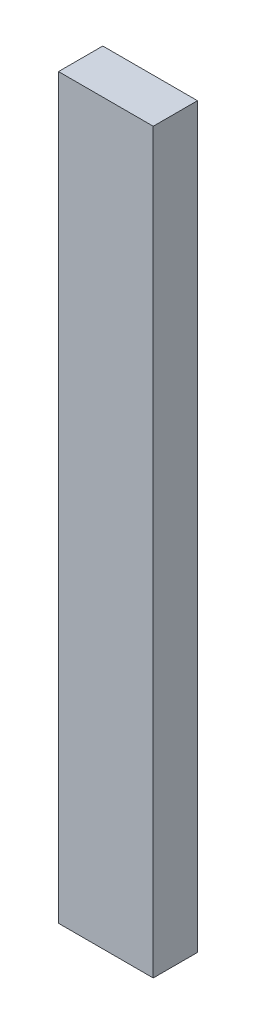
SolidWorks part; units mm, degrees
ref_plane "Front Plane" through (0, 0, 0) normal (0, 0, 1) x (1, 0, 0)
ref_plane "Top Plane" through (0, 0, 0) normal (0, 1, 0) x (1, 0, 0)
ref_plane "Right Plane" through (0, 0, 0) normal (1, 0, 0) x (0, 0, -1)
sketch "Sketch1" plane through (0, 0, 0) normal (0, 0, 1) x (1, 0, 0)
  line L1 (0, 0) -> (6.42, 0)
  line L2 (0, 0) -> (0, 50)
  line L3 (0, 50) -> (6.42, 50)
  line L4 (6.42, 0) -> (6.42, 50)
  dimension "D1" = 6.42
  dimension "D2" = 50
extrude "Boss-Extrude1" add sketch "Sketch1" along normal blind 3
